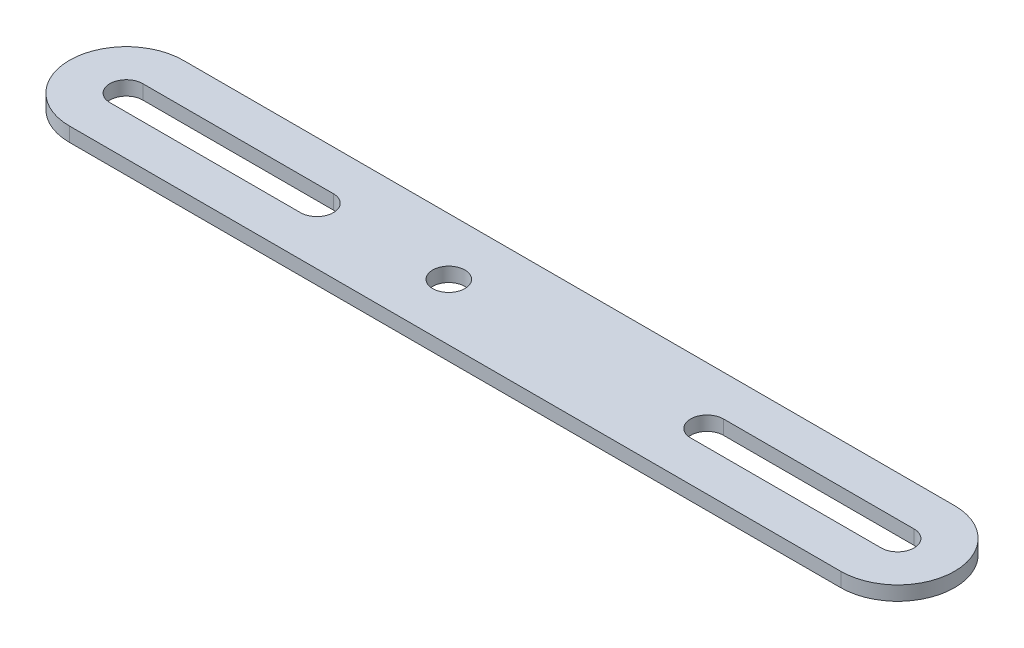
SolidWorks part; units mm, degrees
material "Alumina"
ref_plane "Front Plane" through (0, 0, 0) normal (0, 0, 1) x (1, 0, 0)
ref_plane "Top Plane" through (0, 0, 0) normal (0, 1, 0) x (1, 0, 0)
ref_plane "Right Plane" through (0, 0, 0) normal (1, 0, 0) x (0, 0, -1)
sketch "Sketch1" plane through (0, 0, 0) normal (0, 1, 0) x (1, 0, 0)
  line L0 (-61, 0) -> (61, 0) construction
  line L1 (-61, 9) -> (61, 9)
  line L2 (-61, -9) -> (61, -9)
  line L3 (-61, 0) -> (-30.85, 0) construction
  line L4 (-61, 2.6) -> (-30.85, 2.6)
  line L5 (-61, -2.6) -> (-30.85, -2.6)
  line L6 (61, 0) -> (30.85, 0) construction
  line L7 (61, -2.6) -> (30.85, -2.6)
  line L8 (61, 2.6) -> (30.85, 2.6)
  line L9 (-70, 0) -> (70, 0) construction
  line L10 (-63.6, 0) -> (-63.6, -22.0119) construction
  line L11 (-63.6, -22.0119) -> (63.6, -22.0119) construction
  line L12 (63.6, -22.0119) -> (63.6, 0) construction
  arc A0 (-61, 9) -> (-61, -9) centre (-61, 0) ccw
  arc A1 (61, -9) -> (61, 9) centre (61, 0) ccw
  arc A2 (-61, 2.6) -> (-61, -2.6) centre (-61, 0) ccw
  arc A3 (-30.85, -2.6) -> (-30.85, 2.6) centre (-30.85, 0) ccw
  arc A4 (61, -2.6) -> (61, 2.6) centre (61, 0) ccw
  arc A5 (30.85, 2.6) -> (30.85, -2.6) centre (30.85, 0) ccw
  circle A6 centre (-10, 0) radius 2.55
  point P3 (0, 0)
  point P10 (-45.925, 0)
  point P15 (45.925, 0)
  dimension "D3" = 5.2
  dimension "D1" = 9
  dimension "D5" = 10
  dimension "D6" = 5.1
  dimension "D2" = 122
  dimension "D4" = 30.15
  dimension "D7" = 127.2
extrude "Boss-Extrude1" add sketch "Sketch1" along normal blind 2.25
